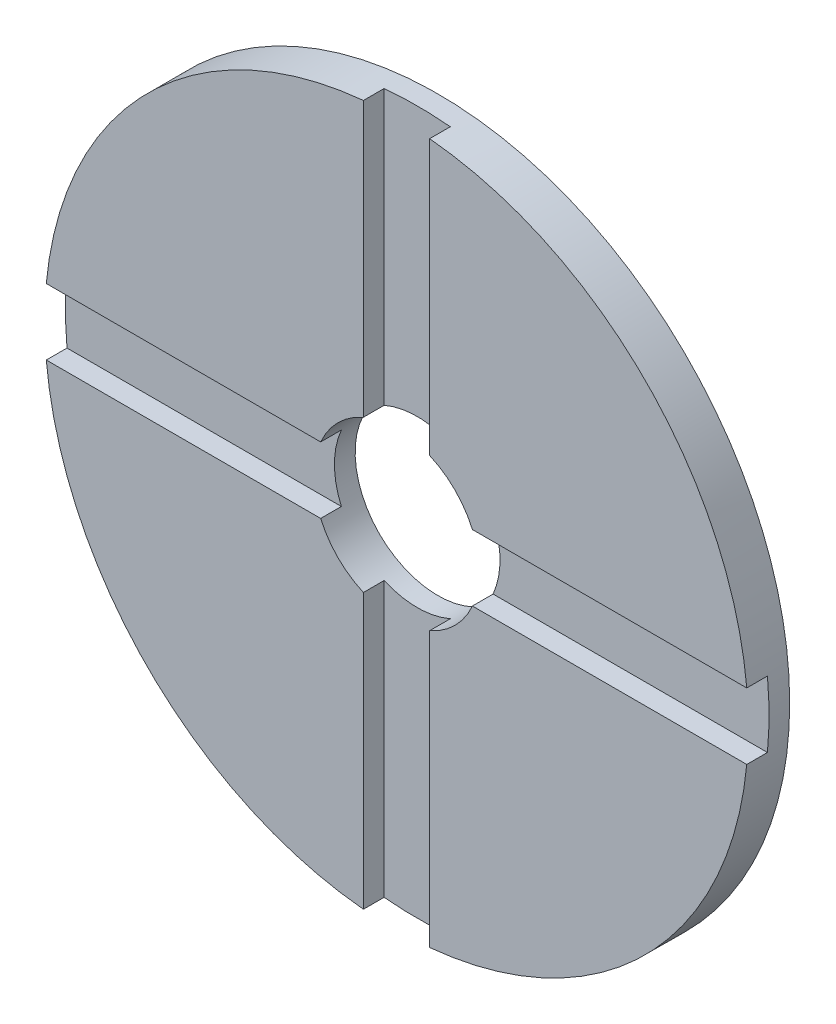
SolidWorks part; units mm, degrees
ref_plane "Front Plane" through (0, 0, 0) normal (0, 0, 1) x (1, 0, 0)
ref_plane "Top Plane" through (0, 0, 0) normal (0, 1, 0) x (1, 0, 0)
ref_plane "Right Plane" through (0, 0, 0) normal (1, 0, 0) x (0, 0, -1)
sketch "Sketch2" plane through (0, 0, 0) normal (0, 0, 1) x (1, 0, 0)
  circle A0 centre (0, 0) radius 85
  circle A1 centre (0, 0) radius 20
  dimension "D1" = 170
  dimension "D2" = 40
extrude "Boss-Extrude1" add sketch "Sketch2" along normal blind 10 contours A0 A1
sketch "Sketch3" plane through (0, 0, 10) normal (0, 0, 1) x (1, 0, 0)
  line L0 (0, 85) -> (0, -85) construction
  line L1 (-85, 0) -> (85, 0) construction
  line L2 (-8, 84.6227) -> (-8, -84.6227)
  line L3 (8, 84.6227) -> (8, -84.6227)
  line L4 (-84.6227, 8) -> (84.6227, 8)
  line L5 (-84.6227, -8) -> (84.6227, -8)
  circle A0 centre (0, 0) radius 85
  circle A1 centre (0, 0) radius 85 construction
  circle M8 centre (0, 0) radius 20
  circle M9 centre (0, 0) radius 85
  dimension "D1" = 16
  dimension "D2" = 16
extrude "Cut-Extrude1" cut sketch "Sketch3" against normal blind 5 contours L5 L4 M9 M8 | L5 L4 M8 M9 | L3 L2 M9 M8 | L3 L2 M8 M9
